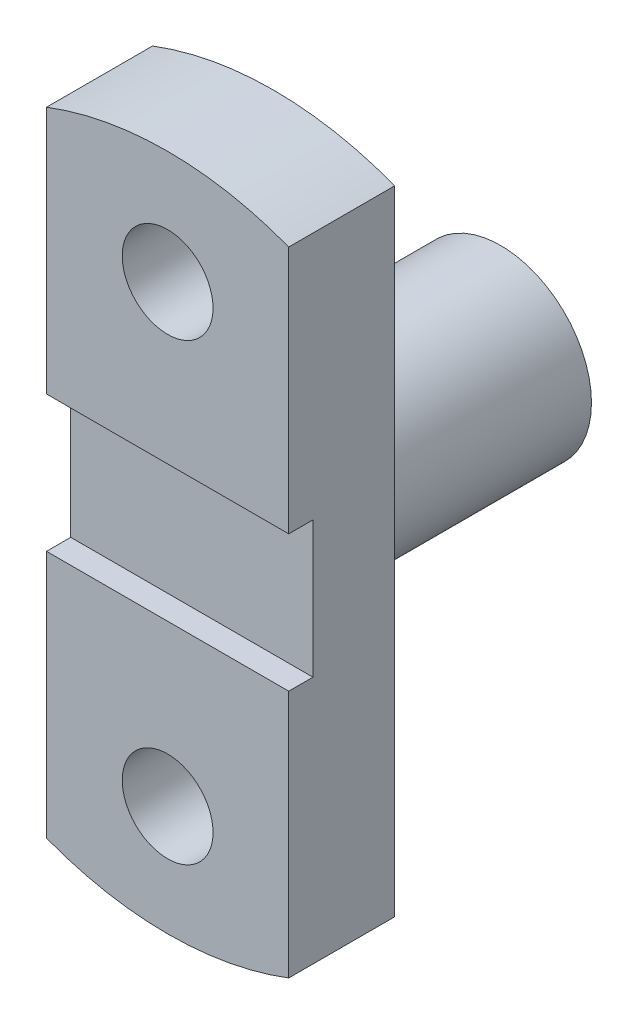
SolidWorks part; units mm, degrees
ref_plane "Front Plane" through (0, 0, 0) normal (0, 0, 1) x (1, 0, 0)
ref_plane "Top Plane" through (0, 0, 0) normal (0, 1, 0) x (1, 0, 0)
ref_plane "Right Plane" through (0, 0, 0) normal (1, 0, 0) x (0, 0, -1)
sketch "Sketch1" plane through (0, 0, 0) normal (0, 0, 1) x (1, 0, 0)
  line L4 (-40, -104.5489) -> (-40, 104.5489)
  line L6 (40, 104.5489) -> (40, -104.5489)
  arc A0 (-40, -104.5489) -> (40, -104.5489) centre (0, 0) ccw
  arc A1 (40, 104.5489) -> (-40, 104.5489) centre (0, 0) ccw
extrude "Boss-Extrude1" add sketch "Sketch1" along normal blind 35
sketch "Sketch2" plane through (0, 0, 0) normal (1, 0, 0) x (0, 0, -1)
  line L0 (-35, 22.5) -> (-35, -22.5)
  line L1 (-35, -104.5489) -> (-35, 104.5489) construction
  line L2 (-35, 22.5) -> (-27, 22.5)
  line L3 (-27, 22.5) -> (-27, -22.5)
  line L4 (-27, -22.5) -> (-35, -22.5)
extrude "Cut-Extrude1" cut sketch "Sketch2" against normal through all and the other way through all
sketch "Sketch3" plane through (0, 0, 0) normal (0, 0, 1) x (1, 0, 0)
  circle A0 centre (0, 74.5489) radius 15
extrude "Cut-Extrude2" cut sketch "Sketch3" against normal through all and the other way through all
sketch "Sketch4" plane through (0, 0, 0) normal (0, 0, 1) x (1, 0, 0)
  circle A0 centre (0, -75.4511) radius 15
extrude "Cut-Extrude3" cut sketch "Sketch4" against normal through all and the other way through all
sketch "Sketch5" plane through (0, 0, 0) normal (0, 0, -1) x (-1, 0, 0)
  circle A0 centre (0, 0) radius 30
extrude "Boss-Extrude2" add sketch "Sketch5" along normal blind 75
